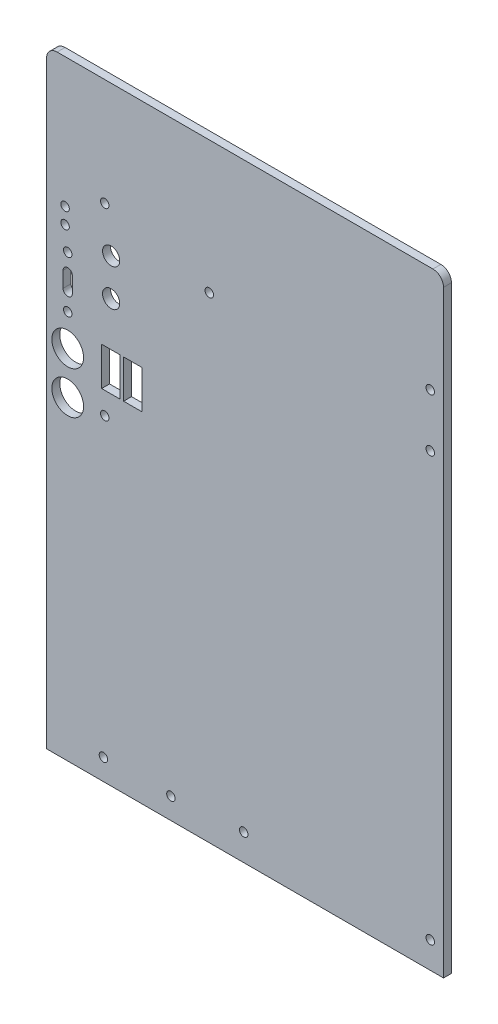
SolidWorks part; units mm, degrees
ref_plane "前视基准面" through (0, 0, 0) normal (0, 0, 1) x (1, 0, 0)
ref_plane "上视基准面" through (0, 0, 0) normal (0, 1, 0) x (1, 0, 0)
ref_plane "右视基准面" through (0, 0, 0) normal (1, 0, 0) x (0, 0, -1)
sketch "草图1" plane through (0, 0, 0) normal (0, 0, 1) x (1, 0, 0)
  line L1 (0, 0) -> (150, 0)
  line L2 (0, 0) -> (0, 230)
  line L3 (0, 230) -> (150, 230)
  line L4 (150, 0) -> (150, 230)
  dimension "D1" = 230
  dimension "D2" = 150
extrude "凸台-拉伸1" add sketch "草图1" along normal blind 3
sketch "草图2" plane through (0, 0, 3) normal (0, 0, 1) x (1, 0, 0)
  line L0 (0, 0) -> (150, 0) construction
  line L1 (0, 230) -> (0, 0) construction
  line L4 (145, 190) -> (145, 170) construction
  line L5 (150, 0) -> (150, 230) construction
  line L6 (150, 230) -> (0, 230) construction
  circle A0 centre (21.5, 8) radius 1.6
  circle A1 centre (47, 8) radius 1.6
  circle A2 centre (74.5, 10) radius 1.6
  circle A3 centre (145, 10) radius 1.6
  circle A4 centre (61.5, 180) radius 1.6
  circle A7 centre (145, 190) radius 1.6
  circle A8 centre (145, 170) radius 1.6
  circle A10 centre (7, 181) radius 1.6
  circle A11 centre (7, 175) radius 1.6
  dimension "D9" = 3.2
  dimension "D13" = 3.2
  dimension "D17" = 49
  dimension "D1" = 8
  dimension "D2" = 21.5
  dimension "D3" = 47
  dimension "D4" = 8
  dimension "D5" = 74.5
  dimension "D6" = 10
  dimension "D7" = 145
  dimension "D8" = 10
  dimension "D10" = 61.5
  dimension "D11" = 180
  dimension "D12" = 20
  dimension "D14" = 5
  dimension "D15" = 40
  dimension "D16" = 7
  dimension "D18" = 6
extrude "切除-拉伸1" cut sketch "草图2" against normal up to next
fillet "圆角1" radius 4 2 edges at (0, 230, 1.5) (150, 230, 1.5)
sketch "草图3" plane through (0, 0, 3) normal (0, 0, 1) x (1, 0, 0)
  line L0 (0, 226) -> (0, 0) construction
  line L1 (0, 0) -> (150, 0) construction
  line L2 (8, 147) -> (8, 166.5) construction
  line L3 (8, 153.8) -> (8, 159.7) construction
  line L4 (6.25, 153.8) -> (6.25, 159.7)
  line L5 (9.75, 153.8) -> (9.75, 159.7)
  circle A0 centre (8, 135) radius 6
  circle A1 centre (8, 119) radius 6
  circle A2 centre (8, 166.5) radius 1.6
  circle A3 centre (8, 147) radius 1.6
  arc A4 (6.25, 153.8) -> (9.75, 153.8) centre (8, 153.8) ccw
  arc A5 (9.75, 159.7) -> (6.25, 159.7) centre (8, 159.7) ccw
  point P12 (8, 156.75)
  point P16 (8, 156.75)
  point P21 (8, 161.45)
  point P22 (8, 152.05)
  dimension "D1" = 12
  dimension "D4" = 12
  dimension "D7" = 3.2
  dimension "D2" = 8
  dimension "D3" = 135
  dimension "D5" = 119
  dimension "D6" = 19.5
  dimension "D8" = 147
  dimension "D9" = 3.5
  dimension "D10" = 9.4
extrude "切除-拉伸2" cut sketch "草图3" against normal up to next
sketch "草图4" plane through (0, 0, 3) normal (0, 0, 1) x (1, 0, 0)
  line L0 (26.82, 141.85) -> (21.82, 129.25) construction
  line L1 (35.12, 141.85) -> (30.12, 129.25) construction
  line L3 (20.82, 128.3) -> (27.82, 128.3)
  line L4 (20.82, 128.3) -> (20.82, 142.8)
  line L5 (20.82, 142.8) -> (27.82, 142.8)
  line L6 (27.82, 128.3) -> (27.82, 142.8)
  line L7 (20.82, 128.3) -> (27.82, 142.8) construction
  line L8 (20.82, 142.8) -> (27.82, 128.3) construction
  line L9 (29.12, 128.3) -> (36.12, 128.3)
  line L10 (29.12, 128.3) -> (29.12, 142.8)
  line L11 (29.12, 142.8) -> (36.12, 142.8)
  line L12 (36.12, 128.3) -> (36.12, 142.8)
  line L13 (29.12, 128.3) -> (36.12, 142.8) construction
  line L14 (29.12, 142.8) -> (36.12, 128.3) construction
  circle A0 centre (22, 120) radius 1.6
  circle A1 centre (22, 189.5) radius 1.6
  circle A2 centre (24.415, 173.5) radius 3.25
  circle A3 centre (24.415, 159.5) radius 3.25
  point P15 (24.32, 135.55)
  point P25 (32.62, 135.55)
  dimension "D4" = 3.2
  dimension "D5" = 6.5
  dimension "D1" = 69.5
  dimension "D2" = 120
  dimension "D3" = 22
  dimension "D6" = 14.5
  dimension "D7" = 7
extrude "切除-拉伸3" cut sketch "草图4" against normal up to next
